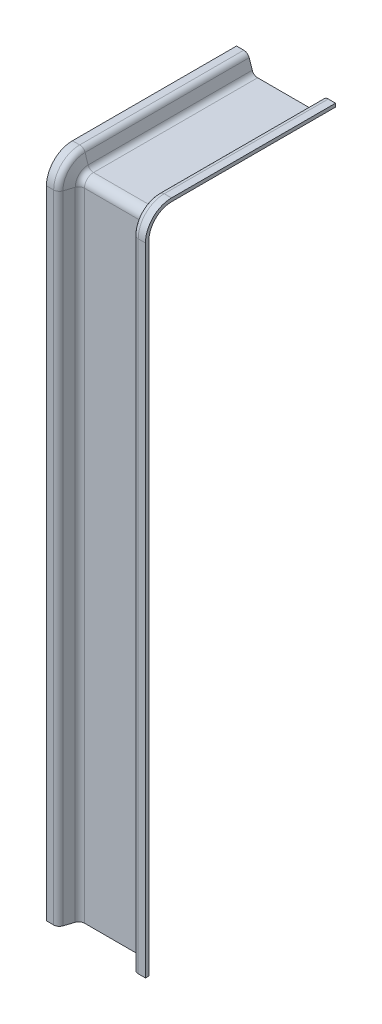
SolidWorks part; units mm, degrees
material "延性铁"
ref_plane "前视基准面" through (0, 0, 0) normal (0, 0, 1) x (1, 0, 0)
ref_plane "上视基准面" through (0, 0, 0) normal (0, 1, 0) x (1, 0, 0)
ref_plane "右视基准面" through (0, 0, 0) normal (1, 0, 0) x (0, 0, -1)
sketch "草图1" plane through (0, 0, 0) normal (0, 1, 0) x (1, 0, 0)
  line L0 (17.5, -7.2) -> (14.9415, -7.2)
  line L1 (13.0442, -5.8325) -> (11.9558, -2.5675)
  line L2 (10.0585, -1.2) -> (-10.0585, -1.2)
  line L3 (17.5, -6) -> (14.9415, -6)
  line L4 (0, -1.2) -> (0, 0) construction
  line L5 (-13.0442, -5.8325) -> (-11.9558, -2.5675)
  line L6 (-17.5, -7.2) -> (-14.9415, -7.2)
  line L7 (14.1826, -5.453) -> (13.0943, -2.1881)
  line L8 (10.0585, 0) -> (-10.0585, 0)
  line L9 (-14.1826, -5.453) -> (-13.0943, -2.1881)
  line L10 (-17.5, -6) -> (-14.9415, -6)
  line L11 (-17.5, -6) -> (-17.5, -7.2)
  line L12 (17.5, -6) -> (17.5, -7.2)
  arc A0 (11.9558, -2.5675) -> (10.0585, -1.2) centre (10.0585, -3.2) ccw
  arc A1 (14.9415, -7.2) -> (13.0442, -5.8325) centre (14.9415, -5.2) cw
  arc A2 (-14.9415, -7.2) -> (-13.0442, -5.8325) centre (-14.9415, -5.2) ccw
  arc A3 (-11.9558, -2.5675) -> (-10.0585, -1.2) centre (-10.0585, -3.2) cw
  arc A4 (14.9415, -6) -> (14.1826, -5.453) centre (14.9415, -5.2) cw
  arc A5 (13.0943, -2.1881) -> (10.0585, 0) centre (10.0585, -3.2) ccw
  arc A6 (-13.0943, -2.1881) -> (-10.0585, 0) centre (-10.0585, -3.2) cw
  arc A7 (-14.9415, -6) -> (-14.1826, -5.453) centre (-14.9415, -5.2) ccw
  point P10 (11.5, -1.2)
  point P13 (13.5, -7.2)
  point P21 (-13.5, -7.2)
  point P22 (-11.5, -1.2)
  dimension "D5" = 2
  dimension "D1" = 35
  dimension "D2" = 6
  dimension "D3" = 11.5
  dimension "D4" = 4
  dimension "D6" = 1.2
sketch "草图2" plane through (0, 0, 0) normal (1, 0, 0) x (0, 0, -1)
  line L0 (0, 225) -> (0, 0)
  line L1 (2, 227) -> (60, 227)
  arc A0 (2, 227) -> (0, 225) centre (2, 225) ccw
  point P6 (0, 227)
  point P7 (0, 227)
  dimension "D3" = 2
  dimension "D1" = 227
  dimension "D2" = 60
sweep "扫描1" add profiles "草图1" path "草图2"
sketch "草图3" plane through (0, 0, 0) normal (1, 0, 0) x (0, 0, -1)
  line L0 (0, 207) -> (20, 227)
  line L1 (0, 225) -> (0, 0) construction
  line L2 (2, 227) -> (60, 227) construction
  dimension "D1" = 45
  dimension "D2" = 20
rib "筋3" sketch "草图3" sketch "草图3" thickness 2 extrusion direction parallel to sketch draft on no parameters "D1"=2
